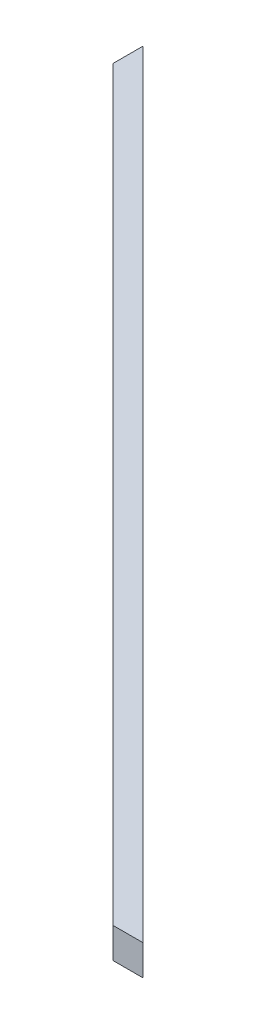
SolidWorks part; units mm, degrees
ref_plane "Front Plane" through (0, 0, 0) normal (0, 0, 1) x (1, 0, 0)
ref_plane "Top Plane" through (0, 0, 0) normal (0, 1, 0) x (1, 0, 0)
ref_plane "Right Plane" through (0, 0, 0) normal (1, 0, 0) x (0, 0, -1)
sketch "Sketch1" plane through (0, 0, 0) normal (0, 1, 0) x (1, 0, 0)
  line L0 (-250, 240) -> (240, -250)
  line L1 (-250, -250) -> (250, -250) construction
  line L2 (-250, -250) -> (-250, 250) construction
  line L3 (-250, 250) -> (250, 250) construction
  line L4 (250, -250) -> (250, 250) construction
  line L5 (-250, -250) -> (250, 250) construction
  line L6 (-250, 250) -> (250, -250) construction
  line L7 (-250, 260) -> (-270, 260) construction
  line L8 (-250, 260) -> (-250, 240) construction
  line L9 (-250, 240) -> (-270, 240) construction
  line L10 (-270, 260) -> (-270, 240) construction
  line L11 (240, -250) -> (260, -250) construction
  line L12 (240, -250) -> (240, -270) construction
  line L13 (240, -270) -> (260, -270) construction
  line L14 (260, -250) -> (260, -270) construction
  line L15 (240, -250) -> (260, -250)
  line L16 (260, -250) -> (-250, 260)
  line L17 (-250, 260) -> (-250, 240)
  point P0 (0, 0)
  point P15 (-250, 250)
  point P16 (250, -250)
  dimension "D1" = 500
  dimension "D2" = 20
extrude "Boss-Extrude1" add sketch "Sketch1" along normal blind 20
